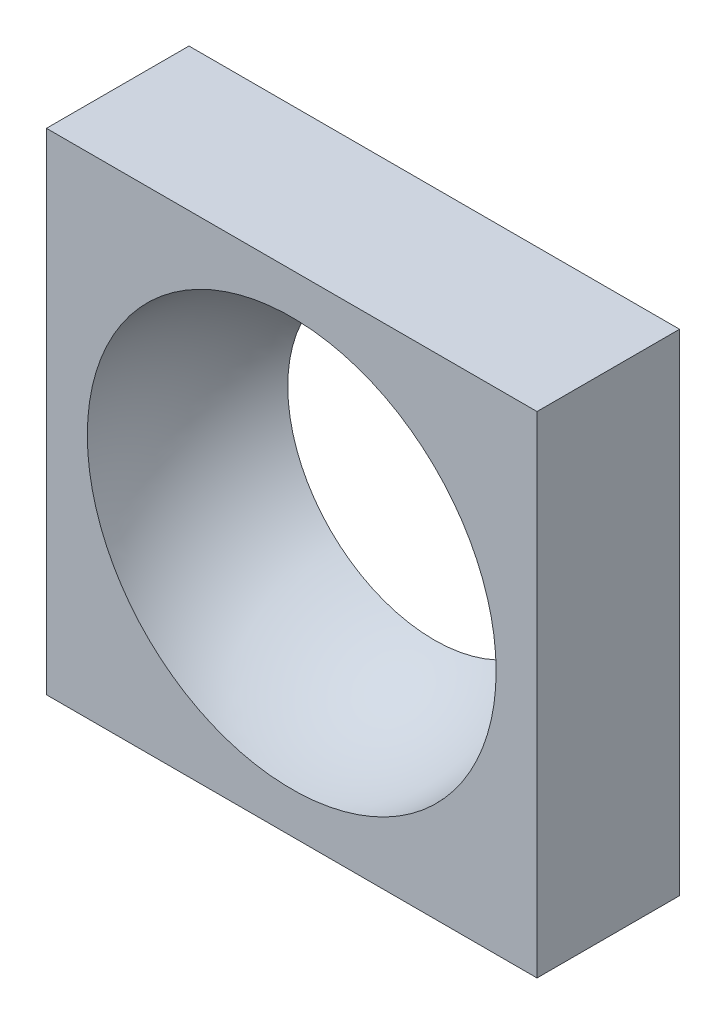
SolidWorks part; units mm, degrees
ref_plane "Front Plane" through (0, 0, 0) normal (0, 0, 1) x (1, 0, 0)
ref_plane "Top Plane" through (0, 0, 0) normal (0, 1, 0) x (1, 0, 0)
ref_plane "Right Plane" through (0, 0, 0) normal (1, 0, 0) x (0, 0, -1)
sketch "Sketch2" plane through (0, 0, 0) normal (0, 0, 1) x (1, 0, 0)
  line L1 (0, 0) -> (24, 0)
  line L2 (0, 0) -> (0, 24)
  line L3 (0, 24) -> (24, 24)
  line L4 (24, 0) -> (24, 24)
  dimension "D1" = 24
  dimension "D2" = 24
extrude "Boss-Extrude1" add sketch "Sketch2" along normal blind 12
sketch "Sketch4" plane through (0, 0, 12) normal (0, 0, 1) x (1, 0, 0)
  line L0 (12, 22) -> (12, 2)
  arc A0 (12, 22) -> (12, 2) centre (12, 12) ccw
revolve "Cut-Revolve1" cut sketch "Sketch4" angle 360 about L0
sketch "Sketch6" plane through (24, 0, 0) normal (1, 0, 0) x (0, 0, -1)
  line L0 (0, 24) -> (-3.0266, 24)
  line L1 (-12, 24) -> (0, 24) construction
  line L2 (0, 0) -> (-3.0266, 0)
  line L3 (-12, 0) -> (0, 0) construction
  line L5 (0, 0) -> (0, 24)
  line L6 (-3.0266, 24) -> (-5.0266, 24)
  line L7 (-5.0266, 24) -> (-5.0266, 0)
  line L8 (-5.0266, 0) -> (-3.0266, 0)
extrude "Cut-Extrude1" cut sketch "Sketch6" against normal through all
